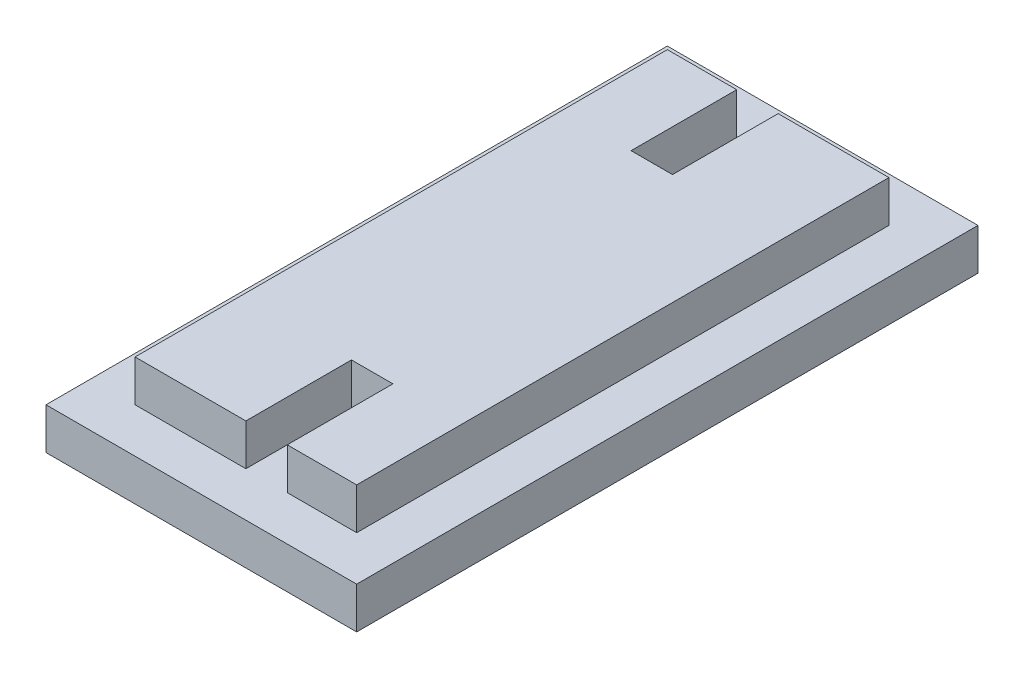
SolidWorks part; units mm, degrees
ref_plane "前视基准面" through (0, 0, 0) normal (0, 0, 1) x (1, 0, 0)
ref_plane "上视基准面" through (0, 0, 0) normal (0, 1, 0) x (1, 0, 0)
ref_plane "右视基准面" through (0, 0, 0) normal (1, 0, 0) x (0, 0, -1)
sketch "Sketch1" plane through (0, 0, 0) normal (0, 1, 0) x (1, 0, 0)
  line L1 (0, 0) -> (15, 0)
  line L2 (0, 0) -> (0, 30)
  line L3 (0, 30) -> (15, 30)
  line L4 (15, 0) -> (15, 30)
extrude "Boss-Extrude1" add sketch "Sketch1" along normal blind 2
sketch "Sketch2" plane through (0, 2, 0) normal (0, 1, 0) x (1, 0, 0)
  line L0 (2.15, 27.85) -> (12.85, 27.85)
  line L1 (0, 30) -> (15, 30) construction
  line L2 (0, 30) -> (0, 0) construction
  line L3 (0, 0) -> (15, 0) construction
  line L4 (15, 30) -> (15, 0) construction
  line L5 (12.85, 27.85) -> (12.85, 2.15)
  line L6 (2.15, 2.15) -> (12.85, 2.15)
  line L7 (2.15, 27.85) -> (2.15, 2.15)
  dimension "D1" = 2.15
extrude "Boss-Extrude2" add sketch "Sketch2" along normal blind 2
sketch "Sketch3" plane through (0, 4, 0) normal (0, 1, 0) x (1, 0, 0)
  line L0 (12.85, 27.85) -> (2.15, 27.85) construction
  line L1 (7.5, 27.85) -> (5.5, 27.85)
  line L2 (7.5, 27.85) -> (7.5, 22.75)
  line L3 (7.5, 22.75) -> (5.5, 22.75)
  line L4 (5.5, 27.85) -> (5.5, 22.75)
  line L5 (2.15, 2.15) -> (12.85, 2.15) construction
  line L6 (7.5, 2.15) -> (9.5, 2.15)
  line L7 (7.5, 2.15) -> (7.5, 7.25)
  line L8 (7.5, 7.25) -> (9.5, 7.25)
  line L9 (9.5, 2.15) -> (9.5, 7.25)
extrude "Cut-Extrude1" cut sketch "Sketch3" against normal blind 2
